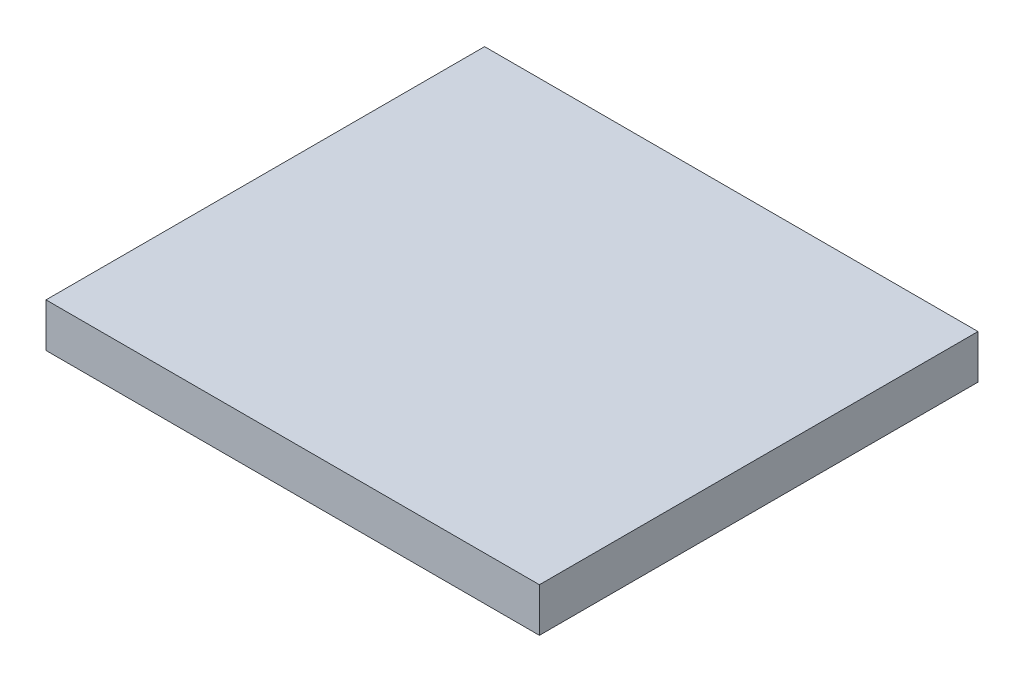
SolidWorks part; units mm, degrees
ref_plane "Ebene vorne" through (0, 0, 0) normal (0, 0, 1) x (1, 0, 0)
ref_plane "Ebene oben" through (0, 0, 0) normal (0, 1, 0) x (1, 0, 0)
ref_plane "Ebene rechts" through (0, 0, 0) normal (1, 0, 0) x (0, 0, -1)
sketch "Skizze1" plane through (0, 0, 0) normal (0, 1, 0) x (1, 0, 0)
  line L1 (-9, -8) -> (9, -8)
  line L2 (-9, -8) -> (-9, 8)
  line L3 (-9, 8) -> (9, 8)
  line L4 (9, -8) -> (9, 8)
  line L5 (-9, -8) -> (9, 8) construction
  line L6 (-9, 8) -> (9, -8) construction
  point P0 (0, 0)
extrude "Aufsatz-Linear austragen1" add sketch "Skizze1" along normal blind 1.6
